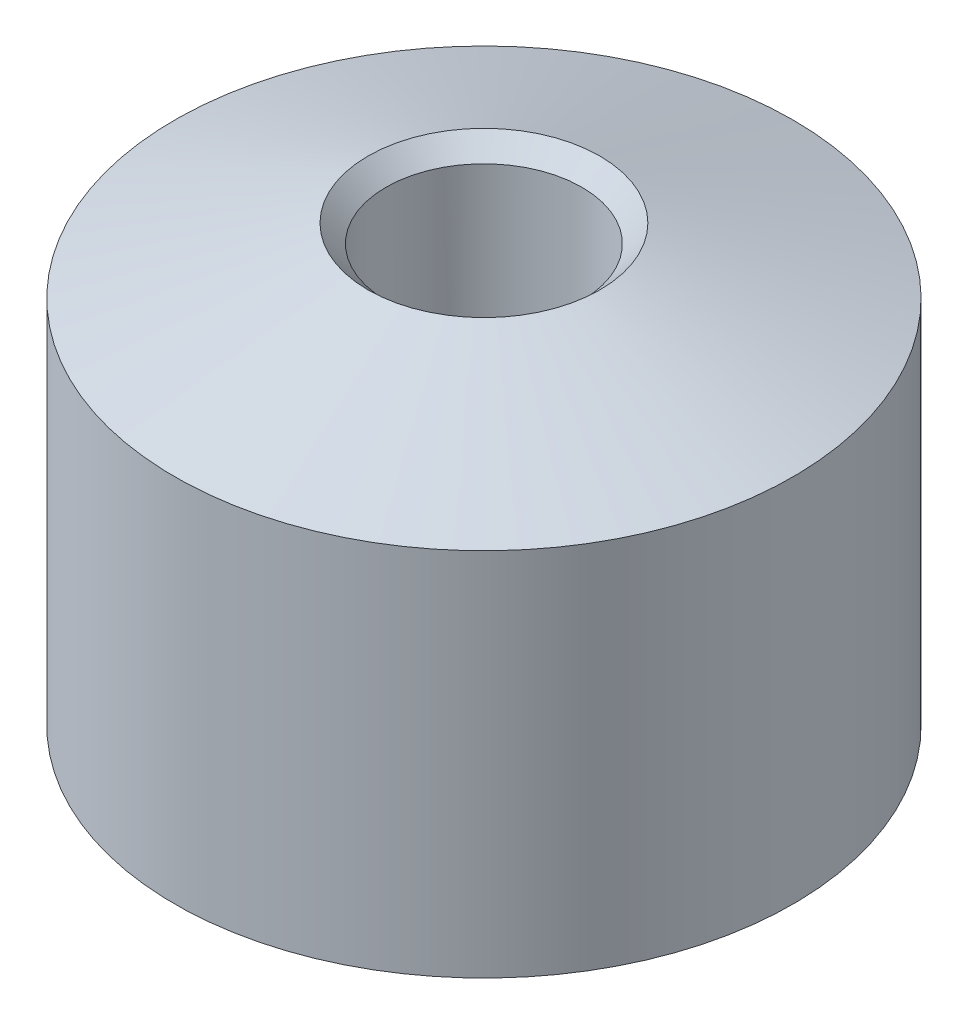
SolidWorks part; units mm, degrees
ref_plane "Front Plane" through (0, 0, 0) normal (0, 0, 1) x (1, 0, 0)
ref_plane "Top Plane" through (0, 0, 0) normal (0, 1, 0) x (1, 0, 0)
ref_plane "Right Plane" through (0, 0, 0) normal (1, 0, 0) x (0, 0, -1)
sketch "Sketch2" plane through (0, 0, 0) normal (0, 0, 1) x (1, 0, 0)
  line L1 (-14.2, 18.5) -> (-4, 18.5)
  line L2 (-14.2, 18.5) -> (-14.2, 35.5)
  line L3 (-4, 37.1734) -> (-5.3266, 38.5)
  line L4 (-14.2, 35.5) -> (-5.3266, 38.5)
  line L7 (-4, 18.5) -> (-4, 37.1734)
  line L11 (0, 15.2) -> (0, 41.79) construction
  line L12 (74.5, 15.2) -> (-74.5, 15.2) construction
  dimension "D2" = 17
revolve "Revolve1" add sketch "Sketch2" angle 360 about L11
sketch "Sketch3" plane through (0, 0, 0) normal (1, 0, 0) x (0, 0, -1)
  circle A0 centre (0, 27.7) radius 4
  dimension "D1" = 8
extrude "Cut-Extrude1" cut sketch "Sketch3" against normal blind 22
sketch "Sketch4" plane through (0, 18.5, 0) normal (0, -1, 0) x (1, 0, 0)
  circle A0 centre (0, 0) radius 4.5
  dimension "D1" = 9
extrude "Cut-Extrude2" cut sketch "Sketch4" against normal blind 32
